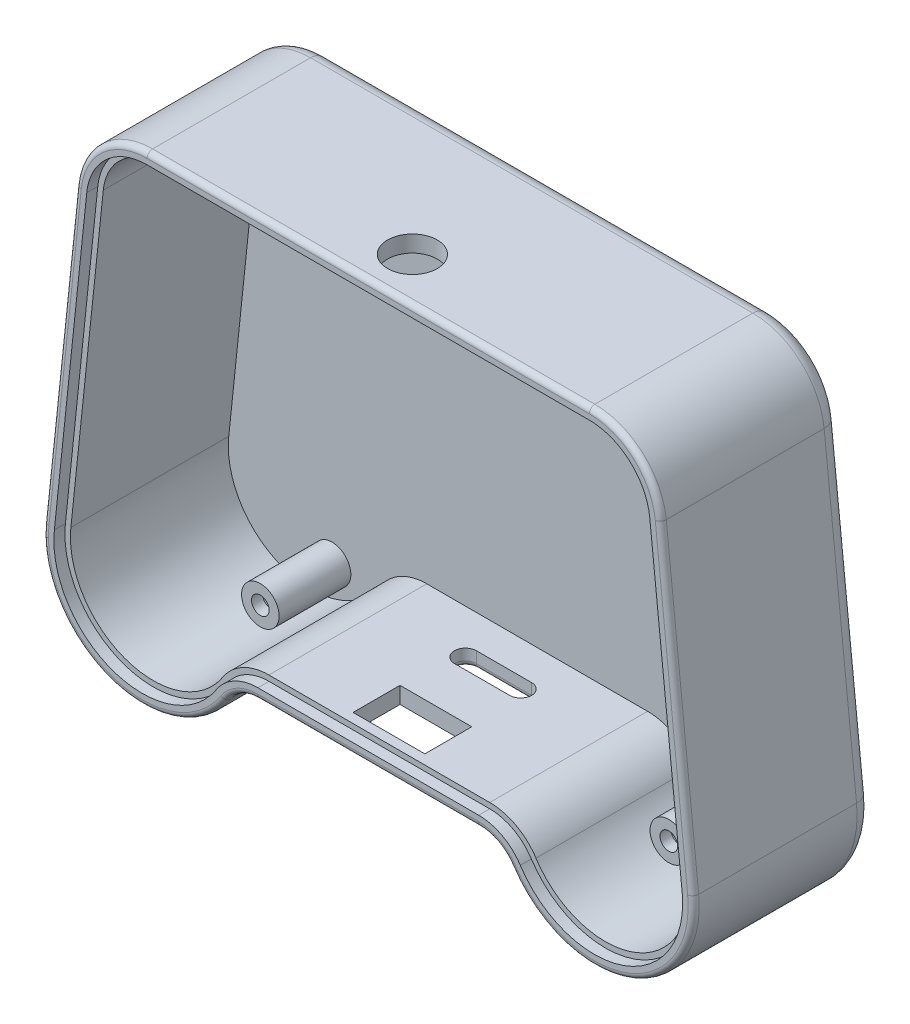
SolidWorks part; units mm, degrees
other "Markup1"
sketch "Sketch18" plane through (58.9509, -52.3196, 41.8483) normal (0.1035, -0.0824, 0.9912) x (0.9946, 0.0158, -0.1025)
ref_plane "Front Plane" through (0, 0, 0) normal (0, 0, 1) x (1, 0, 0)
ref_plane "Top Plane" through (0, 0, 0) normal (0, 1, 0) x (1, 0, 0)
ref_plane "Right Plane" through (0, 0, 0) normal (1, 0, 0) x (0, 0, -1)
sketch "Sketch1" plane through (0, 0, 0) normal (0, 0, 1) x (1, 0, 0)
  line L5 (0, 47.3762) -> (0, -37.96) construction
  line L6 (40.0548, 32.04) -> (-40.0548, 32.04) construction
  line L8 (-50, 23.0853) -> (-55.8687, -32.7516) construction
  line L10 (-20, -37.96) -> (20, -37.96) construction
  line L11 (50, 23.0853) -> (55.8687, -32.7516) construction
  line L12 (40.0548, 33.04) -> (-40.0548, 33.04) construction
  line L13 (-50.9945, 23.1898) -> (-56.8632, -32.6471) construction
  line L14 (-20, -38.96) -> (20, -38.96) construction
  line L15 (50.9945, 23.1898) -> (56.8632, -32.6471) construction
  line L16 (-52.9836, 23.3989) -> (-58.8523, -32.4381)
  line L17 (-20, -40.96) -> (20, -40.96)
  line L18 (52.9836, 23.3989) -> (58.8523, -32.4381)
  line L19 (40.0548, 35.04) -> (-40.0548, 35.04)
  arc A6 (-50, 23.0853) -> (-40.0548, 32.04) centre (-40.0548, 22.04) cw construction
  arc A7 (-55.8687, -32.7516) -> (-28.3803, -42.5038) centre (-40.9509, -34.3196) ccw construction
  arc A8 (-20, -37.96) -> (-28.3803, -42.5038) centre (-20, -47.96) ccw construction
  arc A9 (20, -37.96) -> (28.3803, -42.5038) centre (20, -47.96) cw construction
  arc A10 (55.8687, -32.7516) -> (28.3803, -42.5038) centre (40.9509, -34.3196) cw construction
  arc A11 (50, 23.0853) -> (40.0548, 32.04) centre (40.0548, 22.04) ccw construction
  arc A12 (-50.9945, 23.1898) -> (-40.0548, 33.04) centre (-40.0548, 22.04) cw construction
  arc A13 (-56.8632, -32.6471) -> (-27.5423, -43.0494) centre (-40.9509, -34.3196) ccw construction
  arc A14 (-20, -38.96) -> (-27.5423, -43.0494) centre (-20, -47.96) ccw construction
  arc A15 (20, -38.96) -> (27.5423, -43.0494) centre (20, -47.96) cw construction
  arc A16 (56.8632, -32.6471) -> (27.5423, -43.0494) centre (40.9509, -34.3196) cw construction
  arc A17 (50.9945, 23.1898) -> (40.0548, 33.04) centre (40.0548, 22.04) ccw construction
  arc A18 (-58.8523, -32.4381) -> (-25.8662, -44.1407) centre (-40.9509, -34.3196) ccw
  arc A19 (-20, -40.96) -> (-25.8662, -44.1407) centre (-20, -47.96) ccw
  arc A20 (20, -40.96) -> (25.8662, -44.1407) centre (20, -47.96) cw
  arc A21 (58.8523, -32.4381) -> (25.8662, -44.1407) centre (40.9509, -34.3196) cw
  arc A22 (52.9836, 23.3989) -> (40.0548, 35.04) centre (40.0548, 22.04) ccw
  arc A23 (-52.9836, 23.3989) -> (-40.0548, 35.04) centre (-40.0548, 22.04) cw
  point P23 (0, 32.04)
  dimension "D3" = 15
  dimension "D4" = 10
  dimension "D7" = 40
  dimension "D8" = 1
  dimension "D5" = 50
  dimension "D2" = 10
  dimension "D1" = 96
  dimension "D6" = 70
  dimension "D9" = 3
extrude "Boss-Extrude3" add sketch "Sketch1" along normal blind 32.6 contours A6 L6 A11 L11 A10 A9 L10 A8 A7 L8 | L16 A18 A19 L17 A20 A21 L18 A22 L19 A23
sketch3d "3DSketch4"
  line L0 (40.0548, 33.04, 32.6) -> (-40.0548, 33.04, 32.6)
  line L1 (-50.9945, 23.1898, 32.6) -> (-56.8632, -32.6471, 32.6)
  line L2 (-19.9978, -38.96, 32.6) -> (20, -38.96, 32.6)
  line L3 (56.8627, -32.6423, 32.6) -> (50.9945, 23.1898, 32.6)
  line L4 (40.0548, 33.04, 32.6) -> (-40.0548, 33.04, 32.6)
  line L5 (-50.9945, 23.1898, 32.6) -> (-56.8632, -32.6471, 32.6)
  line L6 (-19.9978, -38.96, 32.6) -> (20, -38.96, 32.6)
  line L7 (56.8627, -32.6423, 32.6) -> (50.9945, 23.1898, 32.6)
  spline S0 degree 5 poles (4026.0326, 466.5237, 32.6) (1610.7553, 177.8242, 32.6) (418.9437, 40.2664, 32.6) (37.2592, 2.7891, 32.6) (52.7665, 14.6378, 32.6) (50.8287, 24.3314, 32.6) (50.7686, 24.5818, 32.6) (50.599, 25.2032, 32.6) (50.3939, 25.8122, 32.6) (50.257, 26.172, 32.6) (49.9531, 26.8788, 32.6) (49.5849, 27.5557, 32.6) (49.3855, 27.8859, 32.6) (48.9583, 28.5281, 32.6) (48.4775, 29.1304, 32.6) (48.2242, 29.421, 32.6) (47.693, 29.9792, 32.6) (47.1147, 30.4888, 32.6) (46.8146, 30.7308, 32.6) (46.194, 31.1879, 32.6) (45.5358, 31.5885, 32.6) (45.1981, 31.7744, 32.6) (44.5075, 32.1166, 32.6) (43.7897, 32.3984, 32.6) (43.4248, 32.5233, 32.6) (42.7618, 32.7171, 32.6) (42.0856, 32.8543, 32.6) (41.7845, 32.9049, 32.6) (41.3067, 32.9701, 32.6) (40.8265, 33.0148, 32.6) (40.6501, 33.0275, 32.6) (33.4483, 33.3643, 32.6) (26.1582, 24.8273, 32.6) (23.0191, 416.4091, 32.6) (27.9081, 1616.2544, 32.6) (44.8886, 4032.7096, 32.6) knots -2.941307 -2.941307 -2.941307 -2.941307 -2.941307 -2.941307 0.039787 0.039787 0.039787 0.11936 0.11936 0.11936 0.238721 0.238721 0.238721 0.358081 0.358081 0.358081 0.477441 0.477441 0.477441 0.596802 0.596802 0.596802 0.716162 0.716162 0.716162 0.835522 0.835522 0.835522 0.930135 0.930135 0.930135 0.984961 0.984961 0.984961 3.166798 3.166798 3.166798 3.166798 3.166798 3.166798 only from (50.9945, 23.1898, 32.6) to (40.0548, 33.04, 32.6)
  spline S1 degree 5 poles (-44.8599, 4032.5752, 32.5998) (-27.9081, 1616.1983, 32.6) (-23.0192, 416.3954, 32.6) (-26.1584, 24.8275, 32.6) (-33.4483, 33.3643, 32.6) (-40.6501, 33.0275, 32.6) (-40.8265, 33.0148, 32.6) (-41.3067, 32.9701, 32.6) (-41.7845, 32.9049, 32.6) (-42.0856, 32.8543, 32.6) (-42.7618, 32.7171, 32.6) (-43.4248, 32.5233, 32.6) (-43.7897, 32.3984, 32.6) (-44.5075, 32.1166, 32.6) (-45.1981, 31.7744, 32.6) (-45.5358, 31.5885, 32.6) (-46.194, 31.1879, 32.6) (-46.8146, 30.7308, 32.6) (-47.1147, 30.4888, 32.6) (-47.693, 29.9792, 32.6) (-48.2242, 29.421, 32.6) (-48.4775, 29.1304, 32.6) (-48.9583, 28.5281, 32.6) (-49.3855, 27.8859, 32.6) (-49.5849, 27.5557, 32.6) (-49.9531, 26.8788, 32.6) (-50.257, 26.172, 32.6) (-50.3939, 25.8122, 32.6) (-50.599, 25.2032, 32.6) (-50.7686, 24.5818, 32.6) (-50.8287, 24.3314, 32.6) (-52.7664, 14.6379, 32.6) (-37.2594, 2.7893, 32.6) (-418.936, 40.2657, 32.6) (-1610.723, 177.8204, 32.6) (-4025.9502, 466.5159, 32.6) knots -2.166772 -2.166772 -2.166772 -2.166772 -2.166772 -2.166772 0.015039 0.015039 0.015039 0.069865 0.069865 0.069865 0.164478 0.164478 0.164478 0.283838 0.283838 0.283838 0.403198 0.403198 0.403198 0.522559 0.522559 0.522559 0.641919 0.641919 0.641919 0.761279 0.761279 0.761279 0.88064 0.88064 0.88064 0.960213 0.960213 0.960213 3.941287 3.941287 3.941287 3.941287 3.941287 3.941287 only from (-40.0548, 33.04, 32.6) to (-50.9945, 23.1898, 32.6)
  spline S2 degree 5 poles (-4035.5742, 373.4906, 32.6) (-1609.1773, 150.6378, 32.6) (-415.2287, 34.684, 32.6) (-36.6156, -10.5501, 32.6) (-56.8177, -21.5664, 32.6) (-56.9726, -34.3215, 32.6) (-56.9628, -34.6959, 32.6) (-56.9094, -35.6313, 32.6) (-56.8017, -36.5597, 32.6) (-56.7157, -37.1131, 32.6) (-56.4971, -38.2106, 32.6) (-56.1779, -39.285, 32.6) (-55.9942, -39.8151, 32.6) (-55.5805, -40.8579, 32.6) (-55.0786, -41.8604, 32.6) (-54.8061, -42.3504, 32.6) (-54.2192, -43.3052, 32.6) (-53.5505, -44.205, 32.6) (-53.1967, -44.64, 32.6) (-52.4519, -45.4781, 32.6) (-51.6368, -46.2477, 32.6) (-51.2127, -46.6145, 32.6) (-50.3335, -47.3101, 32.6) (-49.3968, -47.926, 32.6) (-48.9153, -48.2133, 32.6) (-47.9284, -48.7452, 32.6) (-46.8988, -49.1887, 32.6) (-46.3746, -49.3878, 32.6) (-45.3102, -49.7398, 32.6) (-44.2191, -49.9972, 32.6) (-43.6683, -50.102, 32.6) (-42.5589, -50.2632, 32.6) (-41.4396, -50.3268, 32.6) (-40.8789, -50.3341, 32.6) (-39.7584, -50.2997, 32.6) (-38.6452, -50.1674, 32.6) (-38.0918, -50.0769, 32.6) (-36.9944, -49.848, 32.6) (-35.9211, -49.524, 32.6) (-35.3918, -49.3386, 32.6) (-34.351, -48.9221, 32.6) (-33.3511, -48.4157, 32.6) (-32.8625, -48.1408, 32.6) (-31.9099, -47.5496, 32.6) (-31.0113, -46.8784, 32.6) (-30.5771, -46.5233, 32.6) (-29.8466, -45.868, 32.6) (-29.1732, -45.1553, 32.6) (-28.8943, -44.8404, 32.6) (-28.4745, -44.338, 32.6) (-28.0752, -43.8195, 32.6) (-27.936, -43.6316, 32.6) (-23.2268, -36.9656, 32.6) (-24.9392, -26.0521, 32.6) (306.9363, -236.0672, 32.6) (1311.949, -891.3221, 32.6) (3329.6767, -2216.4598, 32.6) knots -1.425869 -1.425869 -1.425869 -1.425869 -1.425869 -1.425869 0.021854 0.021854 0.021854 0.065562 0.065562 0.065562 0.131123 0.131123 0.131123 0.196685 0.196685 0.196685 0.262247 0.262247 0.262247 0.327809 0.327809 0.327809 0.39337 0.39337 0.39337 0.458932 0.458932 0.458932 0.524494 0.524494 0.524494 0.590056 0.590056 0.590056 0.655617 0.655617 0.655617 0.721179 0.721179 0.721179 0.786741 0.786741 0.786741 0.852302 0.852302 0.852302 0.917864 0.917864 0.917864 0.967097 0.967097 0.967097 0.994475 0.994475 0.994475 1.923407 1.923407 1.923407 1.923407 1.923407 1.923407 only from (-56.8632, -32.6471, 32.6) to (-27.5423, -43.0494, 32.6)
  spline S3 degree 5 poles (-3366.8098, 2158.4119, 32.6002) (-1351.9324, 812.3112, 32.6) (-352.213, 148.9147, 32.6) (-25.983, -61.5448, 32.6) (-31.7137, -48.5409, 32.6) (-27.1386, -42.468, 32.6) (-27.028, -42.3305, 32.6) (-26.7317, -41.9808, 32.6) (-26.4185, -41.6469, 32.6) (-26.219, -41.4485, 32.6) (-25.7808, -41.0447, 32.6) (-25.3082, -40.6807, 32.6) (-25.0498, -40.4996, 32.6) (-24.5177, -40.1605, 32.6) (-23.9585, -39.8678, 32.6) (-23.6729, -39.7338, 32.6) (-23.0908, -39.4919, 32.6) (-22.4898, -39.3051, 32.6) (-22.1852, -39.2244, 32.6) (-21.6721, -39.1096, 32.6) (-21.152, -39.0248, 32.6) (-20.9431, -38.9973, 32.6) (-20.629, -38.9681, 32.6) (-20.0893, -38.9556, 32.6) (-19.759, -38.964, 32.6) (-19.4288, -38.963, 32.6) (-19.0992, -38.9288, 32.6) (54.6133, -4031.8882, 32.6881) knots -4.111071 -4.111071 -4.111071 -4.111071 -4.111071 -4.111071 0.039823 0.039823 0.039823 0.138332 0.138332 0.138332 0.295526 0.295526 0.295526 0.471581 0.471581 0.471581 0.647637 0.647637 0.647637 0.823693 0.823693 0.823693 0.941063 0.941063 0.941063 0.999749 1.125849 1.125849 1.125849 1.125849 1.125849 1.125849 only from (-27.5423, -43.0494, 32.6) to (-19.9978, -38.96, 32.6)
  spline S4 degree 5 poles (52.1433, 3960.623, 32.6) (15.8278, 1530.5109, 32.6) (2.1484, 330.8281, 32.6) (3.4657, -53.7578, 32.6) (12.3549, -38.1998, 32.6) (20.9431, -38.9973, 32.6) (21.152, -39.0248, 32.6) (21.6721, -39.1096, 32.6) (22.1852, -39.2244, 32.6) (22.4898, -39.3051, 32.6) (23.0908, -39.4919, 32.6) (23.6729, -39.7338, 32.6) (23.9585, -39.8678, 32.6) (24.5177, -40.1605, 32.6) (25.0498, -40.4996, 32.6) (25.3082, -40.6807, 32.6) (25.7808, -41.0447, 32.6) (26.219, -41.4485, 32.6) (26.4185, -41.6469, 32.6) (26.7317, -41.9808, 32.6) (27.028, -42.3305, 32.6) (27.1386, -42.468, 32.6) (27.2875, -42.6657, 32.6) (27.4907, -42.9676, 32.6) (27.5914, -43.1262, 32.6) (27.6935, -43.284, 32.6) (27.8023, -43.4372, 32.6) (-3289.0182, -2268.0929, 26.2379) knots -4.639215 -4.639215 -4.639215 -4.639215 -4.639215 -4.639215 0.058697 0.058697 0.058697 0.17609 0.17609 0.17609 0.35218 0.35218 0.35218 0.528269 0.528269 0.528269 0.704359 0.704359 0.704359 0.861583 0.861583 0.861583 0.960111 0.960111 0.960111 0.999942 1.065276 1.065276 1.065276 1.065276 1.065276 1.065276 only from (20, -38.96, 32.6) to (27.5426, -43.0499, 32.6)
  spline S5 degree 5 poles (-3329.9598, -2216.6207, 32.5996) (-1312.0576, -891.3931, 32.6) (-306.9632, -236.0842, 32.6) (24.9393, -26.0516, 32.6) (23.2267, -36.9655, 32.6) (27.936, -43.6316, 32.6) (28.0752, -43.8195, 32.6) (28.4745, -44.338, 32.6) (28.8943, -44.8404, 32.6) (29.1732, -45.1553, 32.6) (29.8466, -45.868, 32.6) (30.5771, -46.5233, 32.6) (31.0113, -46.8784, 32.6) (31.9099, -47.5496, 32.6) (32.8625, -48.1408, 32.6) (33.3511, -48.4157, 32.6) (34.351, -48.9221, 32.6) (35.3918, -49.3386, 32.6) (35.9211, -49.524, 32.6) (36.9944, -49.848, 32.6) (38.0918, -50.0769, 32.6) (38.6452, -50.1674, 32.6) (39.7584, -50.2997, 32.6) (40.8789, -50.3341, 32.6) (41.4396, -50.3268, 32.6) (42.5589, -50.2632, 32.6) (43.6683, -50.102, 32.6) (44.2191, -49.9972, 32.6) (45.3102, -49.7398, 32.6) (46.3746, -49.3878, 32.6) (46.8988, -49.1887, 32.6) (47.9284, -48.7452, 32.6) (48.9153, -48.2133, 32.6) (49.3968, -47.926, 32.6) (50.3335, -47.3101, 32.6) (51.2127, -46.6145, 32.6) (51.6368, -46.2477, 32.6) (52.4519, -45.4781, 32.6) (53.1967, -44.64, 32.6) (53.5505, -44.205, 32.6) (54.2192, -43.3052, 32.6) (54.8061, -42.3504, 32.6) (55.0786, -41.8604, 32.6) (55.5805, -40.8579, 32.6) (55.9942, -39.8151, 32.6) (56.1779, -39.285, 32.6) (56.4971, -38.2106, 32.6) (56.7157, -37.1131, 32.6) (56.8017, -36.5597, 32.6) (56.9094, -35.6313, 32.6) (56.9628, -34.6959, 32.6) (56.9726, -34.3215, 32.6) (56.9658, -33.7608, 32.6) (56.9202, -33.2035, 32.6) (56.8679, -32.6651, 32.6) (56.8034, -32.1278, 32.6) (56.7619, -31.5885, 32.6) (49.5039, -31.8622, 32.6001) (4030.1938, 313.8753, 32.5282) knots -0.923352 -0.923352 -0.923352 -0.923352 -0.923352 -0.923352 0.005512 0.005512 0.005512 0.032888 0.032888 0.032888 0.082115 0.082115 0.082115 0.147671 0.147671 0.147671 0.213226 0.213226 0.213226 0.278781 0.278781 0.278781 0.344336 0.344336 0.344336 0.409891 0.409891 0.409891 0.475446 0.475446 0.475446 0.541001 0.541001 0.541001 0.606557 0.606557 0.606557 0.672112 0.672112 0.672112 0.737667 0.737667 0.737667 0.803222 0.803222 0.803222 0.868777 0.868777 0.868777 0.934332 0.934332 0.934332 0.978036 0.978036 0.978036 0.999887 0.999887 1.041443 1.041443 1.041443 1.041443 1.041443 1.041443 only from (27.5426, -43.0499, 32.6) to (56.8627, -32.6423, 32.6)
  spline S6 degree 5 poles (50.9945, 23.1898, 32.6) (50.9811, 23.3173, 32.6) (50.9677, 23.4448, 32.6) (50.9533, 23.5721, 32.6) (50.9043, 23.9534, 32.6) (50.8287, 24.3314, 32.6) (50.7686, 24.5818, 32.6) (50.599, 25.2032, 32.6) (50.3939, 25.8122, 32.6) (50.257, 26.172, 32.6) (49.9531, 26.8788, 32.6) (49.5849, 27.5557, 32.6) (49.3855, 27.8859, 32.6) (48.9583, 28.5281, 32.6) (48.4775, 29.1304, 32.6) (48.2242, 29.421, 32.6) (47.693, 29.9792, 32.6) (47.1147, 30.4888, 32.6) (46.8146, 30.7308, 32.6) (46.194, 31.1879, 32.6) (45.5358, 31.5885, 32.6) (45.1981, 31.7744, 32.6) (44.5075, 32.1166, 32.6) (43.7897, 32.3984, 32.6) (43.4248, 32.5233, 32.6) (42.7618, 32.7171, 32.6) (42.0856, 32.8543, 32.6) (41.7845, 32.9049, 32.6) (41.3067, 32.9701, 32.6) (40.8265, 33.0148, 32.6) (40.6501, 33.0275, 32.6) (40.4252, 33.038, 32.6) (40.2001, 33.0399, 32.6) (40.1517, 33.04, 32.6) (40.1032, 33.04, 32.6) (40.0548, 33.04, 32.6) knots 0 0 0 0 0 0 0.039787 0.039787 0.039787 0.11936 0.11936 0.11936 0.238721 0.238721 0.238721 0.358081 0.358081 0.358081 0.477441 0.477441 0.477441 0.596802 0.596802 0.596802 0.716162 0.716162 0.716162 0.835522 0.835522 0.835522 0.930135 0.930135 0.930135 0.984961 0.984961 0.984961 1 1 1 1 1 1
  spline S7 degree 5 poles (-40.0548, 33.04, 32.6) (-40.1032, 33.04, 32.6) (-40.1517, 33.04, 32.6) (-40.2001, 33.0399, 32.6) (-40.4252, 33.038, 32.6) (-40.6501, 33.0275, 32.6) (-40.8265, 33.0148, 32.6) (-41.3067, 32.9701, 32.6) (-41.7845, 32.9049, 32.6) (-42.0856, 32.8543, 32.6) (-42.7618, 32.7171, 32.6) (-43.4248, 32.5233, 32.6) (-43.7897, 32.3984, 32.6) (-44.5075, 32.1166, 32.6) (-45.1981, 31.7744, 32.6) (-45.5358, 31.5885, 32.6) (-46.194, 31.1879, 32.6) (-46.8146, 30.7308, 32.6) (-47.1147, 30.4888, 32.6) (-47.693, 29.9792, 32.6) (-48.2242, 29.421, 32.6) (-48.4775, 29.1304, 32.6) (-48.9583, 28.5281, 32.6) (-49.3855, 27.8859, 32.6) (-49.5849, 27.5557, 32.6) (-49.9531, 26.8788, 32.6) (-50.257, 26.172, 32.6) (-50.3939, 25.8122, 32.6) (-50.599, 25.2032, 32.6) (-50.7686, 24.5818, 32.6) (-50.8287, 24.3314, 32.6) (-50.9043, 23.9534, 32.6) (-50.9533, 23.5721, 32.6) (-50.9677, 23.4448, 32.6) (-50.9811, 23.3173, 32.6) (-50.9945, 23.1898, 32.6) knots 0 0 0 0 0 0 0.015039 0.015039 0.015039 0.069865 0.069865 0.069865 0.164478 0.164478 0.164478 0.283838 0.283838 0.283838 0.403198 0.403198 0.403198 0.522559 0.522559 0.522559 0.641919 0.641919 0.641919 0.761279 0.761279 0.761279 0.88064 0.88064 0.88064 0.960213 0.960213 0.960213 1 1 1 1 1 1
  spline S8 degree 5 poles (-56.8632, -32.6471, 32.6) (-56.8827, -32.8325, 32.6) (-56.9022, -33.0179, 32.6) (-56.9202, -33.2035, 32.6) (-56.9658, -33.7608, 32.6) (-56.9726, -34.3215, 32.6) (-56.9628, -34.6959, 32.6) (-56.9094, -35.6313, 32.6) (-56.8017, -36.5597, 32.6) (-56.7157, -37.1131, 32.6) (-56.4971, -38.2106, 32.6) (-56.1779, -39.285, 32.6) (-55.9942, -39.8151, 32.6) (-55.5805, -40.8579, 32.6) (-55.0786, -41.8604, 32.6) (-54.8061, -42.3504, 32.6) (-54.2192, -43.3052, 32.6) (-53.5505, -44.205, 32.6) (-53.1967, -44.64, 32.6) (-52.4519, -45.4781, 32.6) (-51.6368, -46.2477, 32.6) (-51.2127, -46.6145, 32.6) (-50.3335, -47.3101, 32.6) (-49.3968, -47.926, 32.6) (-48.9153, -48.2133, 32.6) (-47.9284, -48.7452, 32.6) (-46.8988, -49.1887, 32.6) (-46.3746, -49.3878, 32.6) (-45.3102, -49.7398, 32.6) (-44.2191, -49.9972, 32.6) (-43.6683, -50.102, 32.6) (-42.5589, -50.2632, 32.6) (-41.4396, -50.3268, 32.6) (-40.8789, -50.3341, 32.6) (-39.7584, -50.2997, 32.6) (-38.6452, -50.1674, 32.6) (-38.0918, -50.0769, 32.6) (-36.9944, -49.848, 32.6) (-35.9211, -49.524, 32.6) (-35.3918, -49.3386, 32.6) (-34.351, -48.9221, 32.6) (-33.3511, -48.4157, 32.6) (-32.8625, -48.1408, 32.6) (-31.9099, -47.5496, 32.6) (-31.0113, -46.8784, 32.6) (-30.5771, -46.5233, 32.6) (-29.8466, -45.868, 32.6) (-29.1732, -45.1553, 32.6) (-28.8943, -44.8404, 32.6) (-28.4745, -44.338, 32.6) (-28.0752, -43.8195, 32.6) (-27.936, -43.6316, 32.6) (-27.774, -43.4023, 32.6) (-27.6195, -43.1679, 32.6) (-27.5937, -43.1284, 32.6) (-27.568, -43.0889, 32.6) (-27.5423, -43.0494, 32.6) knots 0 0 0 0 0 0 0.021854 0.021854 0.021854 0.065562 0.065562 0.065562 0.131123 0.131123 0.131123 0.196685 0.196685 0.196685 0.262247 0.262247 0.262247 0.327809 0.327809 0.327809 0.39337 0.39337 0.39337 0.458932 0.458932 0.458932 0.524494 0.524494 0.524494 0.590056 0.590056 0.590056 0.655617 0.655617 0.655617 0.721179 0.721179 0.721179 0.786741 0.786741 0.786741 0.852302 0.852302 0.852302 0.917864 0.917864 0.917864 0.967097 0.967097 0.967097 0.994475 0.994475 0.994475 1 1 1 1 1 1
  spline S9 degree 5 poles (-27.5423, -43.0494, 32.6) (-27.5035, -42.9898, 32.6) (-27.4647, -42.9302, 32.6) (-27.4255, -42.8707, 32.6) (-27.2875, -42.6657, 32.6) (-27.1386, -42.468, 32.6) (-27.028, -42.3305, 32.6) (-26.7317, -41.9808, 32.6) (-26.4185, -41.6469, 32.6) (-26.219, -41.4485, 32.6) (-25.7808, -41.0447, 32.6) (-25.3082, -40.6807, 32.6) (-25.0498, -40.4996, 32.6) (-24.5177, -40.1605, 32.6) (-23.9585, -39.8678, 32.6) (-23.6729, -39.7338, 32.6) (-23.0908, -39.4919, 32.6) (-22.4898, -39.3051, 32.6) (-22.1852, -39.2244, 32.6) (-21.6721, -39.1096, 32.6) (-21.152, -39.0248, 32.6) (-20.9431, -38.9973, 32.6) (-20.629, -38.9681, 32.6) (-20.3141, -38.9608, 32.6) (-20.2088, -38.96, 32.6) (-20.1035, -38.96, 32.6) (-19.9982, -38.96, 32.6) (-19.9978, -38.96, 32.6) knots 0 0 0 0 0 0 0.039823 0.039823 0.039823 0.138332 0.138332 0.138332 0.295526 0.295526 0.295526 0.471581 0.471581 0.471581 0.647637 0.647637 0.647637 0.823693 0.823693 0.823693 0.941063 0.941063 0.941063 0.999749 1 1 1 1 1 1
  spline S10 degree 5 poles (20, -38.96, 32.6) (20.1049, -38.96, 32.6) (20.2097, -38.96, 32.6) (20.3146, -38.9608, 32.6) (20.629, -38.9681, 32.6) (20.9431, -38.9973, 32.6) (21.152, -39.0248, 32.6) (21.6721, -39.1096, 32.6) (22.1852, -39.2244, 32.6) (22.4898, -39.3051, 32.6) (23.0908, -39.4919, 32.6) (23.6729, -39.7338, 32.6) (23.9585, -39.8678, 32.6) (24.5177, -40.1605, 32.6) (25.0498, -40.4996, 32.6) (25.3082, -40.6807, 32.6) (25.7808, -41.0447, 32.6) (26.219, -41.4485, 32.6) (26.4185, -41.6469, 32.6) (26.7317, -41.9808, 32.6) (27.028, -42.3305, 32.6) (27.1386, -42.468, 32.6) (27.2875, -42.6657, 32.6) (27.4256, -42.8708, 32.6) (27.4648, -42.9303, 32.6) (27.5037, -42.9901, 32.6) (27.5425, -43.0498, 32.6) (27.5426, -43.0499, 32.6) knots 0 0 0 0 0 0 0.058697 0.058697 0.058697 0.17609 0.17609 0.17609 0.35218 0.35218 0.35218 0.528269 0.528269 0.528269 0.704359 0.704359 0.704359 0.861583 0.861583 0.861583 0.960111 0.960111 0.960111 0.999942 1 1 1 1 1 1
  spline S11 degree 5 poles (27.5426, -43.0499, 32.6) (27.5683, -43.0893, 32.6) (27.5939, -43.1287, 32.6) (27.6196, -43.1681, 32.6) (27.774, -43.4023, 32.6) (27.936, -43.6316, 32.6) (28.0752, -43.8195, 32.6) (28.4745, -44.338, 32.6) (28.8943, -44.8404, 32.6) (29.1732, -45.1553, 32.6) (29.8466, -45.868, 32.6) (30.5771, -46.5233, 32.6) (31.0113, -46.8784, 32.6) (31.9099, -47.5496, 32.6) (32.8625, -48.1408, 32.6) (33.3511, -48.4157, 32.6) (34.351, -48.9221, 32.6) (35.3918, -49.3386, 32.6) (35.9211, -49.524, 32.6) (36.9944, -49.848, 32.6) (38.0918, -50.0769, 32.6) (38.6452, -50.1674, 32.6) (39.7584, -50.2997, 32.6) (40.8789, -50.3341, 32.6) (41.4396, -50.3268, 32.6) (42.5589, -50.2632, 32.6) (43.6683, -50.102, 32.6) (44.2191, -49.9972, 32.6) (45.3102, -49.7398, 32.6) (46.3746, -49.3878, 32.6) (46.8988, -49.1887, 32.6) (47.9284, -48.7452, 32.6) (48.9153, -48.2133, 32.6) (49.3968, -47.926, 32.6) (50.3335, -47.3101, 32.6) (51.2127, -46.6145, 32.6) (51.6368, -46.2477, 32.6) (52.4519, -45.4781, 32.6) (53.1967, -44.64, 32.6) (53.5505, -44.205, 32.6) (54.2192, -43.3052, 32.6) (54.8061, -42.3504, 32.6) (55.0786, -41.8604, 32.6) (55.5805, -40.8579, 32.6) (55.9942, -39.8151, 32.6) (56.1779, -39.285, 32.6) (56.4971, -38.2106, 32.6) (56.7157, -37.1131, 32.6) (56.8017, -36.5597, 32.6) (56.9094, -35.6313, 32.6) (56.9628, -34.6959, 32.6) (56.9726, -34.3215, 32.6) (56.9658, -33.7608, 32.6) (56.9202, -33.2035, 32.6) (56.9021, -33.017, 32.6) (56.8825, -32.8306, 32.6) (56.8629, -32.6443, 32.6) (56.8628, -32.6433, 32.6) (56.8627, -32.6423, 32.6) knots 0 0 0 0 0 0 0.005512 0.005512 0.005512 0.032888 0.032888 0.032888 0.082115 0.082115 0.082115 0.147671 0.147671 0.147671 0.213226 0.213226 0.213226 0.278781 0.278781 0.278781 0.344336 0.344336 0.344336 0.409891 0.409891 0.409891 0.475446 0.475446 0.475446 0.541001 0.541001 0.541001 0.606557 0.606557 0.606557 0.672112 0.672112 0.672112 0.737667 0.737667 0.737667 0.803222 0.803222 0.803222 0.868777 0.868777 0.868777 0.934332 0.934332 0.934332 0.978036 0.978036 0.978036 0.999887 0.999887 1 1 1 1 1 1
  dimension "D1" = 2
extrude "Cut-Extrude3" cut sketch "3DSketch4" along direction (0, 0, -1) on the side against the normal blind 2
sketch3d "3DSketch5"
  line L0 (55.8677, -32.742, 30.6) -> (50, 23.0853, 30.6)
  line L1 (40.0548, 32.04, 30.6) -> (-40.0548, 32.04, 30.6)
  line L2 (-50, 23.0853, 30.6) -> (-55.8687, -32.7516, 30.6)
  line L3 (-19.9978, -37.96, 30.6) -> (20, -37.96, 30.6)
  line L4 (55.8677, -32.742, 30.6) -> (50, 23.0853, 30.6)
  line L5 (40.0548, 32.04, 30.6) -> (-40.0548, 32.04, 30.6)
  line L6 (-50, 23.0853, 30.6) -> (-55.8687, -32.7516, 30.6)
  line L7 (-19.9978, -37.96, 30.6) -> (20, -37.96, 30.6)
  spline S0 degree 5 poles (4.0837, 2961.734, 30.6) (-1.8297, 1140.0495, 30.6) (-0.8088, 240.2742, 30.6) (4.8076, -48.6288, 30.6) (12.8669, -37.4364, 30.6) (20.8379, -37.9845, 30.6) (21.0228, -38.0028, 30.6) (21.4838, -38.0607, 30.6) (21.9402, -38.144, 30.6) (22.2122, -38.2031, 30.6) (22.751, -38.3387, 30.6) (23.2804, -38.5089, 30.6) (23.5417, -38.6028, 30.6) (24.0626, -38.8106, 30.6) (24.5666, -39.056, 30.6) (24.8166, -39.1891, 30.6) (25.3101, -39.4746, 30.6) (25.7831, -39.7935, 30.6) (26.0152, -39.9625, 30.6) (26.4698, -40.3201, 30.6) (26.8943, -40.7118, 30.6) (27.1014, -40.9169, 30.6) (27.4359, -41.2696, 30.6) (27.7549, -41.6375, 30.6) (27.8786, -41.7876, 30.6) (32.6646, -47.9948, 30.6) (27.0456, -61.2397, 30.6) (269.9452, 93.8414, 30.6) (1019.3528, 591.8362, 30.6) (2550.601, 1581.6213, 30.6) knots -3.875704 -3.875704 -3.875704 -3.875704 -3.875704 -3.875704 0.04709 0.04709 0.04709 0.140382 0.140382 0.140382 0.280403 0.280403 0.280403 0.419995 0.419995 0.419995 0.562397 0.562397 0.562397 0.706635 0.706635 0.706635 0.853286 0.853286 0.853286 0.950926 0.950926 0.950926 4.793351 4.793351 4.793351 4.793351 4.793351 4.793351 only from (20, -37.96, 30.6) to (28.3806, -42.5043, 30.6)
  spline S1 degree 5 poles (-2485.2015, -1679.5265, 30.6) (-961.8798, -667.1425, 30.6) (-212.4104, -169.4386, 30.6) (29.0654, -17.7104, 30.6) (22.5337, -35.2286, 30.6) (29.2478, -43.7291, 30.6) (29.4647, -43.9837, 30.6) (30.0255, -44.6053, 30.6) (30.6156, -45.1962, 30.6) (30.9816, -45.5376, 30.6) (31.7398, -46.1889, 30.6) (32.5559, -46.769, 30.6) (32.9766, -47.0411, 30.6) (33.8406, -47.5498, 30.6) (34.742, -47.9868, 30.6) (35.2015, -48.1868, 30.6) (36.1357, -48.5481, 30.6) (37.0974, -48.8293, 30.6) (37.5838, -48.9497, 30.6) (38.5657, -49.1498, 30.6) (39.5607, -49.2674, 30.6) (40.0603, -49.3055, 30.6) (41.0616, -49.3401, 30.6) (42.0623, -49.2908, 30.6) (42.5614, -49.2454, 30.6) (43.5546, -49.1131, 30.6) (44.5332, -48.8983, 30.6) (45.0178, -48.7707, 30.6) (45.9752, -48.4753, 30.6) (46.9046, -48.101, 30.6) (47.3612, -47.8946, 30.6) (48.2562, -47.4443, 30.6) (49.1106, -46.9209, 30.6) (49.5266, -46.6415, 30.6) (50.3344, -46.0488, 30.6) (51.09, -45.3908, 30.6) (51.4538, -45.0463, 30.6) (52.1521, -44.3277, 30.6) (52.7878, -43.5532, 30.6) (53.0894, -43.1529, 30.6) (53.6584, -42.3284, 30.6) (54.1567, -41.4595, 30.6) (54.3876, -41.0151, 30.6) (54.8124, -40.107, 30.6) (55.1601, -39.1662, 30.6) (55.3142, -38.6883, 30.6) (55.5812, -37.7219, 30.6) (55.7639, -36.7375, 30.6) (55.8354, -36.2421, 30.6) (55.9236, -35.4114, 30.6) (55.9636, -34.575, 30.6) (55.9697, -34.2402, 30.6) (55.9605, -33.7396, 30.6) (55.919, -33.2419, 30.6) (55.871, -32.7509, 30.6) (55.8124, -32.2608, 30.6) (55.7746, -31.7689, 30.6) (49.7185, -31.9805, 30.6) (3038.8743, 235.1384, 30.5829) knots -1.288413 -1.288413 -1.288413 -1.288413 -1.288413 -1.288413 0.020864 0.020864 0.020864 0.062503 0.062503 0.062503 0.124989 0.124989 0.124989 0.187438 0.187438 0.187438 0.249945 0.249945 0.249945 0.312434 0.312434 0.312434 0.374929 0.374929 0.374929 0.437422 0.437422 0.437422 0.499915 0.499915 0.499915 0.562408 0.562408 0.562408 0.624903 0.624903 0.624903 0.687394 0.687394 0.687394 0.749896 0.749896 0.749896 0.81236 0.81236 0.81236 0.874955 0.874955 0.874955 0.937444 0.937444 0.937444 0.979141 0.979141 0.979141 0.999877 0.999877 1.040815 1.040815 1.040815 1.040815 1.040815 1.040815 only from (28.3806, -42.5043, 30.6) to (55.8677, -32.742, 30.6)
  spline S2 degree 5 poles (3032.7855, 342.3904, 30.6) (1220.342, 132.1734, 30.6) (326.0771, 32.5594, 30.6) (39.7489, 6.1778, 30.6) (51.4247, 15.9144, 30.6) (49.8622, 24.0563, 30.6) (49.8131, 24.2706, 30.6) (49.6746, 24.8022, 30.6) (49.506, 25.3238, 30.6) (49.3935, 25.6323, 30.6) (49.1442, 26.2404, 30.6) (48.8444, 26.8263, 30.6) (48.6821, 27.1133, 30.6) (48.3346, 27.6723, 30.6) (47.9422, 28.2005, 30.6) (47.7357, 28.4559, 30.6) (47.3033, 28.9482, 30.6) (46.8323, 29.4038, 30.6) (46.5882, 29.6214, 30.6) (46.0845, 30.0347, 30.6) (45.5485, 30.4047, 30.6) (45.2739, 30.5783, 30.6) (44.7134, 30.9024, 30.6) (44.129, 31.1824, 30.6) (43.8324, 31.31, 30.6) (43.2294, 31.5393, 30.6) (42.6091, 31.7128, 30.6) (42.2954, 31.7873, 30.6) (41.7679, 31.8939, 30.6) (41.2349, 31.976, 30.6) (41.0211, 32.003, 30.6) (32.9784, 32.727, 30.6) (24.6452, 19.8765, 30.6) (22.9499, 307.1529, 30.6) (34.3615, 1206.859, 30.6) (65.5726, 3031.6398, 30.6) knots -2.712259 -2.712259 -2.712259 -2.712259 -2.712259 -2.712259 0.037063 0.037063 0.037063 0.111821 0.111821 0.111821 0.223808 0.223808 0.223808 0.336097 0.336097 0.336097 0.448019 0.448019 0.448019 0.559379 0.559379 0.559379 0.670066 0.670066 0.670066 0.779999 0.779999 0.779999 0.889985 0.889985 0.889985 0.963279 0.963279 0.963279 3.641298 3.641298 3.641298 3.641298 3.641298 3.641298 only from (50, 23.0853, 30.6) to (40.0548, 32.04, 30.6)
  spline S3 degree 5 poles (-65.6395, 3031.5885, 30.6) (-34.2738, 1206.5589, 30.6) (-22.8162, 306.8723, 30.6) (-24.5382, 19.7446, 30.6) (-32.9362, 32.7423, 30.6) (-41.0386, 32.0018, 30.6) (-41.2563, 31.9738, 30.6) (-41.7989, 31.8888, 30.6) (-42.3355, 31.7782, 30.6) (-42.6546, 31.7009, 30.6) (-43.2852, 31.5209, 30.6) (-43.8977, 31.2834, 30.6) (-44.1987, 31.1513, 30.6) (-44.7897, 30.8623, 30.6) (-45.3556, 30.5281, 30.6) (-45.6317, 30.3497, 30.6) (-46.1671, 29.9719, 30.6) (-46.6694, 29.5506, 30.6) (-46.911, 29.3305, 30.6) (-47.3743, 28.8725, 30.6) (-47.7992, 28.3789, 30.6) (-48.0008, 28.1246, 30.6) (-48.3825, 27.6008, 30.6) (-48.7201, 27.0472, 30.6) (-48.8774, 26.764, 30.6) (-49.168, 26.1866, 30.6) (-49.4102, 25.5882, 30.6) (-49.5195, 25.2848, 30.6) (-49.6834, 24.772, 30.6) (-49.8178, 24.2496, 30.6) (-49.8655, 24.039, 30.6) (-51.4042, 15.9312, 30.6) (-39.9074, 6.2653, 30.6) (-326.4263, 32.4355, 30.6) (-1220.7395, 131.2503, 30.6) (-3032.9252, 339.7721, 30.6) knots -2.659838 -2.659838 -2.659838 -2.659838 -2.659838 -2.659838 0.037392 0.037392 0.037392 0.112013 0.112013 0.112013 0.223996 0.223996 0.223996 0.335918 0.335918 0.335918 0.447939 0.447939 0.447939 0.559299 0.559299 0.559299 0.669885 0.669885 0.669885 0.780189 0.780189 0.780189 0.890179 0.890179 0.890179 0.963612 0.963612 0.963612 3.701508 3.701508 3.701508 3.701508 3.701508 3.701508 only from (-40.0548, 32.04, 30.6) to (-50, 23.0853, 30.6)
  spline S4 degree 5 poles (-3038.5837, 284.9696, 30.6) (-1218.3339, 112.4289, 30.6) (-323.2163, 22.1647, 30.6) (-39.9595, -13.684, 30.6) (-55.774, -23.2698, 30.6) (-55.9699, -34.2447, 30.6) (-55.9636, -34.5795, 30.6) (-55.9231, -35.4157, 30.6) (-55.8347, -36.2463, 30.6) (-55.7632, -36.7416, 30.6) (-55.5803, -37.7258, 30.6) (-55.3131, -38.6921, 30.6) (-55.1589, -39.1698, 30.6) (-54.811, -40.1105, 30.6) (-54.386, -41.0184, 30.6) (-54.155, -41.4627, 30.6) (-53.6566, -42.3314, 30.6) (-53.0874, -43.1556, 30.6) (-52.7858, -43.5558, 30.6) (-52.1499, -44.3301, 30.6) (-51.4516, -45.0485, 30.6) (-51.0877, -45.3929, 30.6) (-50.3321, -46.0507, 30.6) (-49.5242, -46.6432, 30.6) (-49.1082, -46.9224, 30.6) (-48.2538, -47.4457, 30.6) (-47.3588, -47.8957, 30.6) (-46.9022, -48.102, 30.6) (-45.9728, -48.4761, 30.6) (-45.0155, -48.7713, 30.6) (-44.5309, -48.8989, 30.6) (-43.5523, -49.1135, 30.6) (-42.5592, -49.2456, 30.6) (-42.0602, -49.291, 30.6) (-41.0596, -49.3401, 30.6) (-40.0584, -49.3054, 30.6) (-39.5588, -49.2672, 30.6) (-38.564, -49.1495, 30.6) (-37.5822, -48.9494, 30.6) (-37.0958, -48.8289, 30.6) (-36.1343, -48.5476, 30.6) (-35.2002, -48.1863, 30.6) (-34.7408, -47.9863, 30.6) (-33.8395, -47.5492, 30.6) (-32.9756, -47.0405, 30.6) (-32.555, -46.7684, 30.6) (-31.739, -46.1883, 30.6) (-30.9809, -45.537, 30.6) (-30.6149, -45.1956, 30.6) (-30.0249, -44.6047, 30.6) (-29.4643, -43.9832, 30.6) (-29.2474, -43.7285, 30.6) (-23.0831, -35.9233, 30.6) (-28.0805, -20.5195, 30.6) (156.442, -134.3002, 30.6) (717.7495, -531.4731, 30.6) (2907.1813, 240.0746, 30.6) knots -1.306679 -1.306679 -1.306679 -1.306679 -1.306679 -1.306679 0.020737 0.020737 0.020737 0.062436 0.062436 0.062436 0.124931 0.124931 0.124931 0.187534 0.187534 0.187534 0.250006 0.250006 0.250006 0.312516 0.312516 0.312516 0.375016 0.375016 0.375016 0.437518 0.437518 0.437518 0.500019 0.500019 0.500019 0.562521 0.562521 0.562521 0.625022 0.625022 0.625022 0.687525 0.687525 0.687525 0.750022 0.750022 0.750022 0.812537 0.812537 0.812537 0.874994 0.874994 0.874994 0.937489 0.937489 0.937489 0.979133 0.979133 0.979133 2.17815 2.17815 2.17815 2.17815 2.17815 2.17815 only from (-55.8687, -32.7516, 30.6) to (-28.3803, -42.5038, 30.6)
  spline S5 degree 5 poles (319.2254, 2897.6114, 30.6) (-487.1605, 204.3386, 30.6) (-136.965, 10.7482, 30.6) (-29.1482, -55.3165, 30.6) (-31.5195, -46.5479, 30.6) (-27.9019, -41.8184, 30.6) (-27.7846, -41.6745, 30.6) (-27.4824, -41.3215, 30.6) (-27.1656, -40.9825, 30.6) (-26.9696, -40.785, 30.6) (-26.5652, -40.4038, 30.6) (-26.1331, -40.0534, 30.6) (-25.9109, -39.8861, 30.6) (-25.4508, -39.5643, 30.6) (-24.9698, -39.2749, 30.6) (-24.722, -39.1375, 30.6) (-24.2142, -38.8793, 30.6) (-23.6885, -38.6591, 30.6) (-23.4204, -38.5578, 30.6) (-22.8725, -38.3728, 30.6) (-22.3136, -38.2263, 30.6) (-22.0292, -38.1622, 30.6) (-21.5516, -38.0715, 30.6) (-21.0688, -38.0077, 30.6) (-20.8752, -37.9873, 30.6) (-12.8161, -37.3972, 30.6) (-4.6387, -49.013, 30.6) (0.4363, 239.4792, 30.6) (-0.4128, 1139.2539, 30.6) (-10.2055, 2961.7648, 30.6) knots -2.853023 -2.853023 -2.853023 -2.853023 -2.853023 -2.853023 0.0469 0.0469 0.0469 0.14009 0.14009 0.14009 0.280092 0.280092 0.280092 0.419846 0.419846 0.419846 0.562289 0.562289 0.562289 0.706312 0.706312 0.706312 0.852992 0.852992 0.852992 0.950693 0.950693 0.950693 4.913586 4.913586 4.913586 4.913586 4.913586 4.913586 only from (-28.3803, -42.5038, 30.6) to (-19.9978, -37.96, 30.6)
  spline S6 degree 5 poles (20, -37.96, 30.6) (20.0935, -37.96, 30.6) (20.187, -37.96, 30.6) (20.2805, -37.9605, 30.6) (20.5593, -37.9653, 30.6) (20.8379, -37.9845, 30.6) (21.0228, -38.0028, 30.6) (21.4838, -38.0607, 30.6) (21.9402, -38.144, 30.6) (22.2122, -38.2031, 30.6) (22.751, -38.3387, 30.6) (23.2804, -38.5089, 30.6) (23.5417, -38.6028, 30.6) (24.0626, -38.8106, 30.6) (24.5666, -39.056, 30.6) (24.8166, -39.1891, 30.6) (25.3101, -39.4746, 30.6) (25.7831, -39.7935, 30.6) (26.0152, -39.9625, 30.6) (26.4698, -40.3201, 30.6) (26.8943, -40.7118, 30.6) (27.1014, -40.9169, 30.6) (27.4359, -41.2696, 30.6) (27.7549, -41.6375, 30.6) (27.8786, -41.7876, 30.6) (28.0568, -42.0187, 30.6) (28.2206, -42.2596, 30.6) (28.2743, -42.3409, 30.6) (28.3275, -42.4226, 30.6) (28.3806, -42.5043, 30.6) knots 0 0 0 0 0 0 0.04709 0.04709 0.04709 0.140382 0.140382 0.140382 0.280403 0.280403 0.280403 0.419995 0.419995 0.419995 0.562397 0.562397 0.562397 0.706635 0.706635 0.706635 0.853286 0.853286 0.853286 0.950926 0.950926 0.950926 1 1 1 1 1 1
  spline S7 degree 5 poles (28.3806, -42.5043, 30.6) (28.4717, -42.6441, 30.6) (28.5628, -42.784, 30.6) (28.6549, -42.9232, 30.6) (28.9372, -43.3358, 30.6) (29.2478, -43.7291, 30.6) (29.4647, -43.9837, 30.6) (30.0255, -44.6053, 30.6) (30.6156, -45.1962, 30.6) (30.9816, -45.5376, 30.6) (31.7398, -46.1889, 30.6) (32.5559, -46.769, 30.6) (32.9766, -47.0411, 30.6) (33.8406, -47.5498, 30.6) (34.742, -47.9868, 30.6) (35.2015, -48.1868, 30.6) (36.1357, -48.5481, 30.6) (37.0974, -48.8293, 30.6) (37.5838, -48.9497, 30.6) (38.5657, -49.1498, 30.6) (39.5607, -49.2674, 30.6) (40.0603, -49.3055, 30.6) (41.0616, -49.3401, 30.6) (42.0623, -49.2908, 30.6) (42.5614, -49.2454, 30.6) (43.5546, -49.1131, 30.6) (44.5332, -48.8983, 30.6) (45.0178, -48.7707, 30.6) (45.9752, -48.4753, 30.6) (46.9046, -48.101, 30.6) (47.3612, -47.8946, 30.6) (48.2562, -47.4443, 30.6) (49.1106, -46.9209, 30.6) (49.5266, -46.6415, 30.6) (50.3344, -46.0488, 30.6) (51.09, -45.3908, 30.6) (51.4538, -45.0463, 30.6) (52.1521, -44.3277, 30.6) (52.7878, -43.5532, 30.6) (53.0894, -43.1529, 30.6) (53.6584, -42.3284, 30.6) (54.1567, -41.4595, 30.6) (54.3876, -41.0151, 30.6) (54.8124, -40.107, 30.6) (55.1601, -39.1662, 30.6) (55.3142, -38.6883, 30.6) (55.5812, -37.7219, 30.6) (55.7639, -36.7375, 30.6) (55.8354, -36.2421, 30.6) (55.9236, -35.4114, 30.6) (55.9636, -34.575, 30.6) (55.9697, -34.2402, 30.6) (55.9605, -33.7396, 30.6) (55.919, -33.2419, 30.6) (55.9028, -33.0759, 30.6) (55.8853, -32.9099, 30.6) (55.8679, -32.7439, 30.6) (55.8678, -32.743, 30.6) (55.8677, -32.742, 30.6) knots 0 0 0 0 0 0 0.020864 0.020864 0.020864 0.062503 0.062503 0.062503 0.124989 0.124989 0.124989 0.187438 0.187438 0.187438 0.249945 0.249945 0.249945 0.312434 0.312434 0.312434 0.374929 0.374929 0.374929 0.437422 0.437422 0.437422 0.499915 0.499915 0.499915 0.562408 0.562408 0.562408 0.624903 0.624903 0.624903 0.687394 0.687394 0.687394 0.749896 0.749896 0.749896 0.81236 0.81236 0.81236 0.874955 0.874955 0.874955 0.937444 0.937444 0.937444 0.979141 0.979141 0.979141 0.999877 0.999877 1 1 1 1 1 1
  spline S8 degree 5 poles (50, 23.0853, 30.6) (49.9887, 23.1932, 30.6) (49.9773, 23.3012, 30.6) (49.9652, 23.4091, 30.6) (49.9241, 23.734, 30.6) (49.8622, 24.0563, 30.6) (49.8131, 24.2706, 30.6) (49.6746, 24.8022, 30.6) (49.506, 25.3238, 30.6) (49.3935, 25.6323, 30.6) (49.1442, 26.2404, 30.6) (48.8444, 26.8263, 30.6) (48.6821, 27.1133, 30.6) (48.3346, 27.6723, 30.6) (47.9422, 28.2005, 30.6) (47.7357, 28.4559, 30.6) (47.3033, 28.9482, 30.6) (46.8323, 29.4038, 30.6) (46.5882, 29.6214, 30.6) (46.0845, 30.0347, 30.6) (45.5485, 30.4047, 30.6) (45.2739, 30.5783, 30.6) (44.7134, 30.9024, 30.6) (44.129, 31.1824, 30.6) (43.8324, 31.31, 30.6) (43.2294, 31.5393, 30.6) (42.6091, 31.7128, 30.6) (42.2954, 31.7873, 30.6) (41.7679, 31.8939, 30.6) (41.2349, 31.976, 30.6) (41.0211, 32.003, 30.6) (40.6995, 32.032, 30.6) (40.3774, 32.0392, 30.6) (40.2699, 32.04, 30.6) (40.1623, 32.04, 30.6) (40.0548, 32.04, 30.6) knots 0 0 0 0 0 0 0.037063 0.037063 0.037063 0.111821 0.111821 0.111821 0.223808 0.223808 0.223808 0.336097 0.336097 0.336097 0.448019 0.448019 0.448019 0.559379 0.559379 0.559379 0.670066 0.670066 0.670066 0.779999 0.779999 0.779999 0.889985 0.889985 0.889985 0.963279 0.963279 0.963279 1 1 1 1 1 1
  spline S9 degree 5 poles (-40.0548, 32.04, 30.6) (-40.1643, 32.04, 30.6) (-40.2738, 32.04, 30.6) (-40.3833, 32.0392, 30.6) (-40.7112, 32.0317, 30.6) (-41.0386, 32.0018, 30.6) (-41.2563, 31.9738, 30.6) (-41.7989, 31.8888, 30.6) (-42.3355, 31.7782, 30.6) (-42.6546, 31.7009, 30.6) (-43.2852, 31.5209, 30.6) (-43.8977, 31.2834, 30.6) (-44.1987, 31.1513, 30.6) (-44.7897, 30.8623, 30.6) (-45.3556, 30.5281, 30.6) (-45.6317, 30.3497, 30.6) (-46.1671, 29.9719, 30.6) (-46.6694, 29.5506, 30.6) (-46.911, 29.3305, 30.6) (-47.3743, 28.8725, 30.6) (-47.7992, 28.3789, 30.6) (-48.0008, 28.1246, 30.6) (-48.3825, 27.6008, 30.6) (-48.7201, 27.0472, 30.6) (-48.8774, 26.764, 30.6) (-49.168, 26.1866, 30.6) (-49.4102, 25.5882, 30.6) (-49.5195, 25.2848, 30.6) (-49.6834, 24.772, 30.6) (-49.8178, 24.2496, 30.6) (-49.8655, 24.039, 30.6) (-49.9256, 23.7223, 30.6) (-49.9659, 23.4032, 30.6) (-49.9777, 23.2973, 30.6) (-49.9889, 23.1913, 30.6) (-50, 23.0853, 30.6) knots 0 0 0 0 0 0 0.037392 0.037392 0.037392 0.112013 0.112013 0.112013 0.223996 0.223996 0.223996 0.335918 0.335918 0.335918 0.447939 0.447939 0.447939 0.559299 0.559299 0.559299 0.669885 0.669885 0.669885 0.780189 0.780189 0.780189 0.890179 0.890179 0.890179 0.963612 0.963612 0.963612 1 1 1 1 1 1
  spline S10 degree 5 poles (-55.8687, -32.7516, 30.6) (-55.886, -32.9166, 30.6) (-55.9034, -33.0815, 30.6) (-55.9195, -33.2466, 30.6) (-55.9609, -33.7442, 30.6) (-55.9699, -34.2447, 30.6) (-55.9636, -34.5795, 30.6) (-55.9231, -35.4157, 30.6) (-55.8347, -36.2463, 30.6) (-55.7632, -36.7416, 30.6) (-55.5803, -37.7258, 30.6) (-55.3131, -38.6921, 30.6) (-55.1589, -39.1698, 30.6) (-54.811, -40.1105, 30.6) (-54.386, -41.0184, 30.6) (-54.155, -41.4627, 30.6) (-53.6566, -42.3314, 30.6) (-53.0874, -43.1556, 30.6) (-52.7858, -43.5558, 30.6) (-52.1499, -44.3301, 30.6) (-51.4516, -45.0485, 30.6) (-51.0877, -45.3929, 30.6) (-50.3321, -46.0507, 30.6) (-49.5242, -46.6432, 30.6) (-49.1082, -46.9224, 30.6) (-48.2538, -47.4457, 30.6) (-47.3588, -47.8957, 30.6) (-46.9022, -48.102, 30.6) (-45.9728, -48.4761, 30.6) (-45.0155, -48.7713, 30.6) (-44.5309, -48.8989, 30.6) (-43.5523, -49.1135, 30.6) (-42.5592, -49.2456, 30.6) (-42.0602, -49.291, 30.6) (-41.0596, -49.3401, 30.6) (-40.0584, -49.3054, 30.6) (-39.5588, -49.2672, 30.6) (-38.564, -49.1495, 30.6) (-37.5822, -48.9494, 30.6) (-37.0958, -48.8289, 30.6) (-36.1343, -48.5476, 30.6) (-35.2002, -48.1863, 30.6) (-34.7408, -47.9863, 30.6) (-33.8395, -47.5492, 30.6) (-32.9756, -47.0405, 30.6) (-32.555, -46.7684, 30.6) (-31.739, -46.1883, 30.6) (-30.9809, -45.537, 30.6) (-30.6149, -45.1956, 30.6) (-30.0249, -44.6047, 30.6) (-29.4643, -43.9832, 30.6) (-29.2474, -43.7285, 30.6) (-28.9368, -43.3353, 30.6) (-28.6546, -42.9227, 30.6) (-28.5625, -42.7836, 30.6) (-28.4714, -42.6437, 30.6) (-28.3803, -42.5038, 30.6) knots 0 0 0 0 0 0 0.020737 0.020737 0.020737 0.062436 0.062436 0.062436 0.124931 0.124931 0.124931 0.187534 0.187534 0.187534 0.250006 0.250006 0.250006 0.312516 0.312516 0.312516 0.375016 0.375016 0.375016 0.437518 0.437518 0.437518 0.500019 0.500019 0.500019 0.562521 0.562521 0.562521 0.625022 0.625022 0.625022 0.687525 0.687525 0.687525 0.750022 0.750022 0.750022 0.812537 0.812537 0.812537 0.874994 0.874994 0.874994 0.937489 0.937489 0.937489 0.979133 0.979133 0.979133 1 1 1 1 1 1
  spline S11 degree 5 poles (-28.3803, -42.5038, 30.6) (-28.3295, -42.4258, 30.6) (-28.2787, -42.3477, 30.6) (-28.2274, -42.27, 30.6) (-28.0712, -42.0398, 30.6) (-27.9019, -41.8184, 30.6) (-27.7846, -41.6745, 30.6) (-27.4824, -41.3215, 30.6) (-27.1656, -40.9825, 30.6) (-26.9696, -40.785, 30.6) (-26.5652, -40.4038, 30.6) (-26.1331, -40.0534, 30.6) (-25.9109, -39.8861, 30.6) (-25.4508, -39.5643, 30.6) (-24.9698, -39.2749, 30.6) (-24.722, -39.1375, 30.6) (-24.2142, -38.8793, 30.6) (-23.6885, -38.6591, 30.6) (-23.4204, -38.5578, 30.6) (-22.8725, -38.3728, 30.6) (-22.3136, -38.2263, 30.6) (-22.0292, -38.1622, 30.6) (-21.5516, -38.0715, 30.6) (-21.0688, -38.0077, 30.6) (-20.8752, -37.9873, 30.6) (-20.5835, -37.966, 30.6) (-20.2915, -37.9606, 30.6) (-20.1936, -37.96, 30.6) (-20.0957, -37.96, 30.6) (-19.9978, -37.96, 30.6) knots 0 0 0 0 0 0 0.0469 0.0469 0.0469 0.14009 0.14009 0.14009 0.280092 0.280092 0.280092 0.419846 0.419846 0.419846 0.562289 0.562289 0.562289 0.706312 0.706312 0.706312 0.852992 0.852992 0.852992 0.950693 0.950693 0.950693 1 1 1 1 1 1
  dimension "D1" = 1
extrude "Cut-Extrude4" cut sketch "3DSketch5" along direction (0, 0, -1) on the side against the normal blind 28.6
fillet "Fillet3" radius 3 10 edges at (-55.9179, -4.5196, 0) (-46.9693, -51.2836, 0) (-23.3365, -41.8063, 0) (0, -40.96, 0) (23.3365, -41.8063, 0) (46.9693, -51.2836, 0) (55.9179, -4.5196, 0) (48.7535, 31.7009, 0) (0, 35.04, 0) (-48.7535, 31.7009, 0)
sketch "Sketch4" plane through (0, 0, 2) normal (0, 0, 1) x (1, 0, 0)
  line L0 (-50.2675, 25.04) -> (10.3371, 25.04) construction
  line L1 (0, 32.04) -> (0, -37.96) construction
  line L3 (-43, 50.8201) -> (-43, -72.3102) construction
  line L4 (40.0548, 32.04) -> (-40.0548, 32.04) construction
  line L6 (0, -2.96) -> (60.013, -2.96) construction
  line L7 (40.0548, 32.04) -> (-40.0548, 32.04) construction
  line L10 (-19.9978, -37.96) -> (20, -37.96) construction
  circle A0 centre (-43, 25.04) radius 3.5
  circle A1 centre (43, 25.04) radius 3.5
  circle A2 centre (43, -30.96) radius 3.5
  dimension "D5" = 7
  dimension "D1" = 7
  dimension "D2" = 43
extrude "Boss-Extrude4" add sketch "Sketch4" along normal blind 13
sketch "Sketch5" plane through (0, 32.04, 0) normal (0, -1, 0) x (-1, 0, 0)
  line L0 (0, -2) -> (0, -41.8483) construction
  line L1 (-40.0548, -2) -> (40.0548, -2) construction
  line L2 (25.2765, -24.6) -> (-24.9664, -24.6) construction
  dimension "D1" = 22.6
sketch "Sketch6" plane through (0, 32.04, 0) normal (0, -1, 0) x (-1, 0, 0)
  line L0 (0, -2) -> (0, -41.8483) construction
  line L1 (25.2765, -24.6) -> (-24.9664, -24.6) construction
  circle A0 centre (0, -24.6) radius 4.5
  dimension "D1" = 9
extrude "Cut-Extrude5" cut sketch "Sketch6" against normal blind 13
sketch "Sketch7" plane through (0, -37.96, 0) normal (0, 1, 0) x (1, 0, 0)
  line L0 (0, -2) -> (0, -50.3308) construction
  line L1 (-19.9978, -2) -> (20, -2) construction
  line L2 (5, -10) -> (-5, -10) construction
  line L3 (5, -12) -> (-5, -12)
  line L4 (5, -8) -> (-5, -8)
  arc A0 (5, -12) -> (5, -8) centre (5, -10) ccw
  arc A1 (-5, -8) -> (-5, -12) centre (-5, -10) ccw
  point P7 (0, -10)
  dimension "D1" = 8
  dimension "D2" = 10
  dimension "D3" = 0
  dimension "D4" = 2
extrude "Cut-Extrude6" cut sketch "Sketch7" against normal blind 13
sketch "Sketch10" plane through (0, 0, 2) normal (0, 0, 1) x (1, 0, 0)
  line L0 (-50.1025, 22.1105) -> (-20.2028, 19.6594) construction
  line L1 (-50, 23.0853) -> (-55.8687, -32.7516) construction
  line L2 (-20.2028, 19.6594) -> (-24.8598, -37.15) construction
  line L3 (-24.8598, -37.15) -> (-55.9569, -34.6008) construction
  line L4 (-24.8598, -37.15) -> (-55.6792, -37.15) construction
  line L5 (-50, 23.0853) -> (-50, -37.15) construction
  line L6 (-50, -37.15) -> (-48, -37.15)
  line L12 (-50, -35.15) -> (-50, -37.15)
  line L13 (-50, -35.15) -> (-48, -35.15)
  line L14 (-48, -35.15) -> (-48, -37.15)
  circle A0 centre (-43, 25.04) radius 3.5 construction
  spline S0 degree 5 poles (-55.8687, -32.7516) (-55.886, -32.9166) (-55.9034, -33.0815) (-55.9195, -33.2466) (-55.9609, -33.7442) (-55.9699, -34.2447) (-55.9636, -34.5795) (-55.9231, -35.4157) (-55.8347, -36.2463) (-55.7632, -36.7416) (-55.5803, -37.7258) (-55.3131, -38.6921) (-55.1589, -39.1698) (-54.811, -40.1105) (-54.386, -41.0184) (-54.155, -41.4627) (-53.6566, -42.3314) (-53.0874, -43.1556) (-52.7858, -43.5558) (-52.1499, -44.3301) (-51.4516, -45.0485) (-51.0877, -45.3929) (-50.3321, -46.0507) (-49.5242, -46.6432) (-49.1082, -46.9224) (-48.2538, -47.4457) (-47.3588, -47.8957) (-46.9022, -48.102) (-45.9728, -48.4761) (-45.0155, -48.7713) (-44.5309, -48.8989) (-43.5523, -49.1135) (-42.5592, -49.2456) (-42.0602, -49.291) (-41.0596, -49.3401) (-40.0584, -49.3054) (-39.5588, -49.2672) (-38.564, -49.1495) (-37.5822, -48.9494) (-37.0958, -48.8289) (-36.1343, -48.5476) (-35.2002, -48.1863) (-34.7408, -47.9863) (-33.8395, -47.5492) (-32.9756, -47.0405) (-32.555, -46.7684) (-31.739, -46.1883) (-30.9809, -45.537) (-30.6149, -45.1956) (-30.0249, -44.6047) (-29.4643, -43.9832) (-29.2474, -43.7285) (-28.9368, -43.3353) (-28.6546, -42.9227) (-28.5625, -42.7836) (-28.4714, -42.6437) (-28.3803, -42.5038) knots 0 0 0 0 0 0 0.020737 0.020737 0.020737 0.062436 0.062436 0.062436 0.124931 0.124931 0.124931 0.187534 0.187534 0.187534 0.250006 0.250006 0.250006 0.312516 0.312516 0.312516 0.375016 0.375016 0.375016 0.437518 0.437518 0.437518 0.500019 0.500019 0.500019 0.562521 0.562521 0.562521 0.625022 0.625022 0.625022 0.687525 0.687525 0.687525 0.750022 0.750022 0.750022 0.812537 0.812537 0.812537 0.874994 0.874994 0.874994 0.937489 0.937489 0.937489 0.979133 0.979133 0.979133 1 1 1 1 1 1 construction
  spline S1 degree 5 poles (-55.8687, -32.7516) (-55.886, -32.9166) (-55.9034, -33.0815) (-55.9195, -33.2466) (-55.9609, -33.7442) (-55.9699, -34.2447) (-55.9636, -34.5795) (-55.9231, -35.4157) (-55.8347, -36.2463) (-55.7632, -36.7416) (-55.5803, -37.7258) (-55.3131, -38.6921) (-55.1589, -39.1698) (-54.811, -40.1105) (-54.386, -41.0184) (-54.155, -41.4627) (-53.6566, -42.3314) (-53.0874, -43.1556) (-52.7858, -43.5558) (-52.1499, -44.3301) (-51.4516, -45.0485) (-51.0877, -45.3929) (-50.3321, -46.0507) (-49.5242, -46.6432) (-49.1082, -46.9224) (-48.2538, -47.4457) (-47.3588, -47.8957) (-46.9022, -48.102) (-45.9728, -48.4761) (-45.0155, -48.7713) (-44.5309, -48.8989) (-43.5523, -49.1135) (-42.5592, -49.2456) (-42.0602, -49.291) (-41.0596, -49.3401) (-40.0584, -49.3054) (-39.5588, -49.2672) (-38.564, -49.1495) (-37.5822, -48.9494) (-37.0958, -48.8289) (-36.1343, -48.5476) (-35.2002, -48.1863) (-34.7408, -47.9863) (-33.8395, -47.5492) (-32.9756, -47.0405) (-32.555, -46.7684) (-31.739, -46.1883) (-30.9809, -45.537) (-30.6149, -45.1956) (-30.0249, -44.6047) (-29.4643, -43.9832) (-29.2474, -43.7285) (-28.9368, -43.3353) (-28.6546, -42.9227) (-28.5625, -42.7836) (-28.4714, -42.6437) (-28.3803, -42.5038) knots 0 0 0 0 0 0 0.020737 0.020737 0.020737 0.062436 0.062436 0.062436 0.124931 0.124931 0.124931 0.187534 0.187534 0.187534 0.250006 0.250006 0.250006 0.312516 0.312516 0.312516 0.375016 0.375016 0.375016 0.437518 0.437518 0.437518 0.500019 0.500019 0.500019 0.562521 0.562521 0.562521 0.625022 0.625022 0.625022 0.687525 0.687525 0.687525 0.750022 0.750022 0.750022 0.812537 0.812537 0.812537 0.874994 0.874994 0.874994 0.937489 0.937489 0.937489 0.979133 0.979133 0.979133 1 1 1 1 1 1 construction
  dimension "D1" = 57
  dimension "D2" = 30
  dimension "D3" = 2
  dimension "D4" = 2
sketch "Sketch12" plane through (0, 0, 15) normal (0, 0, 1) x (1, 0, 0)
  line L0 (0, 32.04) -> (0, -30.96) construction
  line L1 (40.0548, 32.04) -> (-40.0548, 32.04) construction
  circle A0 centre (-43, 25.04) radius 1.4
  circle A5 centre (43, 25.04) radius 1.4
  circle A6 centre (43, 25.04) radius 1.4
  circle A8 centre (43, -30.96) radius 1.4
  circle A9 centre (43, -30.96) radius 1.4
  dimension "D1" = 2.1
  dimension "D2" = 2.1
extrude "Cut-Extrude7" cut sketch "Sketch12" against normal blind 13
sketch "Sketch14" plane through (0, 0, 2) normal (0, 0, 1) x (1, 0, 0)
  line L0 (-19.9978, -37.96) -> (-55.5021, -37.96) construction
  line L1 (-0.155, -2.8958) -> (-47.1864, -2.8958) construction
  line L2 (-19.9978, -37.96) -> (20, -37.96) construction
  line L4 (-37.155, -37.96) -> (-37.155, -48.8315) construction
  line L5 (-0.155, 32.04) -> (-0.155, -37.8315) construction
  line L6 (-25.2765, 32.04) -> (24.9664, 32.04) construction
  circle A0 centre (-37.155, -43.3958) radius 3.4
  circle A1 centre (36.845, -43.3958) radius 3.4
  spline S0 degree 5 poles (-55.8687, -32.7516) (-55.886, -32.9166) (-55.9034, -33.0815) (-55.9195, -33.2466) (-55.9609, -33.7442) (-55.9699, -34.2447) (-55.9636, -34.5795) (-55.9231, -35.4157) (-55.8347, -36.2463) (-55.7632, -36.7416) (-55.5803, -37.7258) (-55.3131, -38.6921) (-55.1589, -39.1698) (-54.811, -40.1105) (-54.386, -41.0184) (-54.155, -41.4627) (-53.6566, -42.3314) (-53.0874, -43.1556) (-52.7858, -43.5558) (-52.1499, -44.3301) (-51.4516, -45.0485) (-51.0877, -45.3929) (-50.3321, -46.0507) (-49.5242, -46.6432) (-49.1082, -46.9224) (-48.2538, -47.4457) (-47.3588, -47.8957) (-46.9022, -48.102) (-45.9728, -48.4761) (-45.0155, -48.7713) (-44.5309, -48.8989) (-43.5523, -49.1135) (-42.5592, -49.2456) (-42.0602, -49.291) (-41.0596, -49.3401) (-40.0584, -49.3054) (-39.5588, -49.2672) (-38.564, -49.1495) (-37.5822, -48.9494) (-37.0958, -48.8289) (-36.1343, -48.5476) (-35.2002, -48.1863) (-34.7408, -47.9863) (-33.8395, -47.5492) (-32.9756, -47.0405) (-32.555, -46.7684) (-31.739, -46.1883) (-30.9809, -45.537) (-30.6149, -45.1956) (-30.0249, -44.6047) (-29.4643, -43.9832) (-29.2474, -43.7285) (-28.9368, -43.3353) (-28.6546, -42.9227) (-28.5625, -42.7836) (-28.4714, -42.6437) (-28.3803, -42.5038) knots 0 0 0 0 0 0 0.020737 0.020737 0.020737 0.062436 0.062436 0.062436 0.124931 0.124931 0.124931 0.187534 0.187534 0.187534 0.250006 0.250006 0.250006 0.312516 0.312516 0.312516 0.375016 0.375016 0.375016 0.437518 0.437518 0.437518 0.500019 0.500019 0.500019 0.562521 0.562521 0.562521 0.625022 0.625022 0.625022 0.687525 0.687525 0.687525 0.750022 0.750022 0.750022 0.812537 0.812537 0.812537 0.874994 0.874994 0.874994 0.937489 0.937489 0.937489 0.979133 0.979133 0.979133 1 1 1 1 1 1 construction
  spline S1 degree 5 poles (-28.3803, -42.5038) (-28.3295, -42.4258) (-28.2787, -42.3477) (-28.2274, -42.27) (-28.0712, -42.0398) (-27.9019, -41.8184) (-27.7846, -41.6745) (-27.4824, -41.3215) (-27.1656, -40.9825) (-26.9696, -40.785) (-26.5652, -40.4038) (-26.1331, -40.0534) (-25.9109, -39.8861) (-25.4508, -39.5643) (-24.9698, -39.2749) (-24.722, -39.1375) (-24.2142, -38.8793) (-23.6885, -38.6591) (-23.4204, -38.5578) (-22.8725, -38.3728) (-22.3136, -38.2263) (-22.0292, -38.1622) (-21.5516, -38.0715) (-21.0688, -38.0077) (-20.8752, -37.9873) (-20.5835, -37.966) (-20.2915, -37.9606) (-20.1936, -37.96) (-20.0957, -37.96) (-19.9978, -37.96) knots 0 0 0 0 0 0 0.0469 0.0469 0.0469 0.14009 0.14009 0.14009 0.280092 0.280092 0.280092 0.419846 0.419846 0.419846 0.562289 0.562289 0.562289 0.706312 0.706312 0.706312 0.852992 0.852992 0.852992 0.950693 0.950693 0.950693 1 1 1 1 1 1 construction
  spline S2 degree 5 poles (-55.8687, -32.7516) (-55.886, -32.9166) (-55.9034, -33.0815) (-55.9195, -33.2466) (-55.9609, -33.7442) (-55.9699, -34.2447) (-55.9636, -34.5795) (-55.9231, -35.4157) (-55.8347, -36.2463) (-55.7632, -36.7416) (-55.5803, -37.7258) (-55.3131, -38.6921) (-55.1589, -39.1698) (-54.811, -40.1105) (-54.386, -41.0184) (-54.155, -41.4627) (-53.6566, -42.3314) (-53.0874, -43.1556) (-52.7858, -43.5558) (-52.1499, -44.3301) (-51.4516, -45.0485) (-51.0877, -45.3929) (-50.3321, -46.0507) (-49.5242, -46.6432) (-49.1082, -46.9224) (-48.2538, -47.4457) (-47.3588, -47.8957) (-46.9022, -48.102) (-45.9728, -48.4761) (-45.0155, -48.7713) (-44.5309, -48.8989) (-43.5523, -49.1135) (-42.5592, -49.2456) (-42.0602, -49.291) (-41.0596, -49.3401) (-40.0584, -49.3054) (-39.5588, -49.2672) (-38.564, -49.1495) (-37.5822, -48.9494) (-37.0958, -48.8289) (-36.1343, -48.5476) (-35.2002, -48.1863) (-34.7408, -47.9863) (-33.8395, -47.5492) (-32.9756, -47.0405) (-32.555, -46.7684) (-31.739, -46.1883) (-30.9809, -45.537) (-30.6149, -45.1956) (-30.0249, -44.6047) (-29.4643, -43.9832) (-29.2474, -43.7285) (-28.9368, -43.3353) (-28.6546, -42.9227) (-28.5625, -42.7836) (-28.4714, -42.6437) (-28.3803, -42.5038) knots 0 0 0 0 0 0 0.020737 0.020737 0.020737 0.062436 0.062436 0.062436 0.124931 0.124931 0.124931 0.187534 0.187534 0.187534 0.250006 0.250006 0.250006 0.312516 0.312516 0.312516 0.375016 0.375016 0.375016 0.437518 0.437518 0.437518 0.500019 0.500019 0.500019 0.562521 0.562521 0.562521 0.625022 0.625022 0.625022 0.687525 0.687525 0.687525 0.750022 0.750022 0.750022 0.812537 0.812537 0.812537 0.874994 0.874994 0.874994 0.937489 0.937489 0.937489 0.979133 0.979133 0.979133 1 1 1 1 1 1 construction
  dimension "D2" = 6.8
  dimension "D1" = 37
  dimension "D3" = 40.5
extrude "Boss-Extrude6" add sketch "Sketch14" along normal blind 13
sketch "Sketch15" plane through (0, 0, 15) normal (0, 0, 1) x (1, 0, 0)
  line L0 (-0.155, 32.04) -> (-0.155, -45.7022) construction
  line L1 (-25.2765, 32.04) -> (24.9664, 32.04) construction
  circle A0 centre (-37.155, -43.3958) radius 1.6
  circle A1 centre (36.845, -43.3958) radius 1.6
extrude "Cut-Extrude8" cut sketch "Sketch15" against normal blind 14
sketch "Sketch16" plane through (0, 0, 2) normal (0, 0, 1) x (1, 0, 0)
  line L0 (-0.155, 32.04) -> (-0.155, -52.4004) construction
  line L1 (-25.2765, 32.04) -> (24.9664, 32.04) construction
  circle A0 centre (-37.155, -43.3958) radius 2.7
  circle A1 centre (36.845, -43.3958) radius 2.7
extrude "Cut-Extrude9" cut sketch "Sketch16" against normal blind 12 and the other way blind 11
sketch "Sketch17" plane through (0, -37.96, 0) normal (0, 1, 0) x (1, 0, 0)
  line L0 (0, -20.35) -> (0, -5.8772) construction
  line L1 (-6.5, -20.35) -> (6.5, -20.35)
  line L2 (-6.5, -20.35) -> (-6.5, -28.85)
  line L3 (-6.5, -28.85) -> (6.5, -28.85)
  line L4 (6.5, -20.35) -> (6.5, -28.85)
  line L5 (0, -2) -> (0, -41.8483) construction
  line L6 (-6.5, -24.6) -> (11.8256, -24.6) construction
  line L7 (-25.2765, -24.6) -> (24.9664, -24.6) construction
  dimension "D1" = 8.5
  dimension "D2" = 13
extrude "Cut-Extrude10" cut sketch "Sketch17" against normal blind 3
fillet "Fillet8" radius 1 10 edges at (-48.7535, 31.7009, 32.6) (0, 35.04, 32.6) (48.7535, 31.7009, 32.6) (55.9179, -4.5196, 32.6) (46.9693, -51.2836, 32.6) (23.3365, -41.8063, 32.6) (0, -40.96, 32.6) (-23.3365, -41.8063, 32.6) (-46.9693, -51.2836, 32.6) (-55.9179, -4.5196, 32.6)
fillet "Fillet10" radius 1 4 edges at (7, -40.96, 10) (0, -40.96, 12) (-7, -40.96, 10) (0, -40.96, 8)
